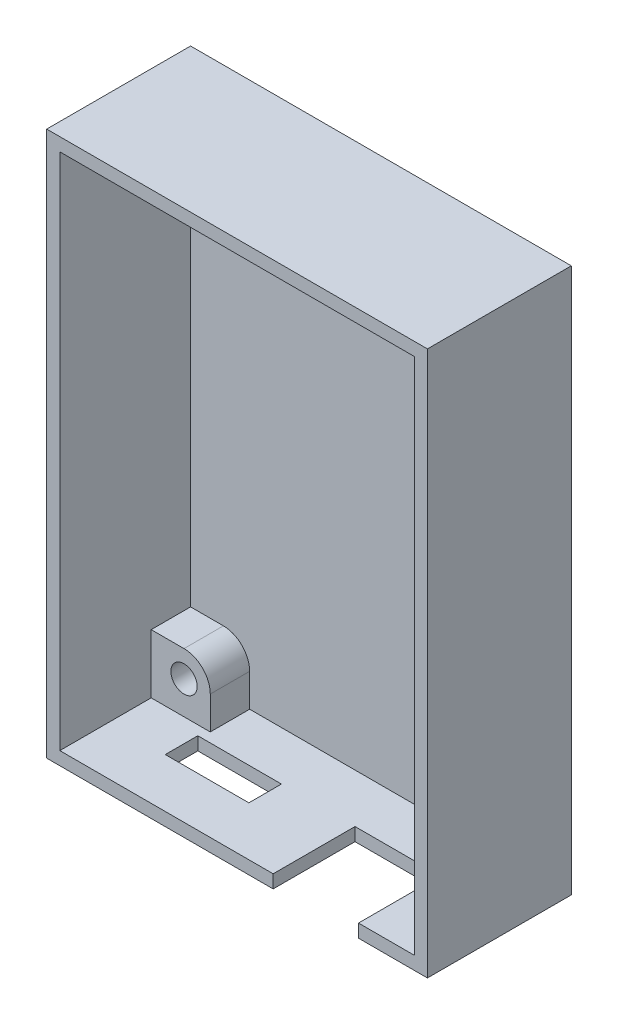
SolidWorks part; units mm, degrees
ref_plane "Front Plane" through (0, 0, 0) normal (1, 0, 0) x (0, 1, 0)
ref_plane "Top Plane" through (0, 0, 0) normal (0, 0, 1) x (0, 1, 0)
ref_plane "Right Plane" through (0, 0, 0) normal (0, 1, 0) x (-1, 0, 0)
sketch "Sketch1" plane through (0, 0, 0) normal (0, 0, 1) x (0, 1, 0)
  line L1 (-41.5, 29) -> (41.5, 29)
  line L2 (-41.5, 29) -> (-41.5, -29)
  line L3 (-41.5, -29) -> (41.5, -29)
  line L4 (41.5, 29) -> (41.5, -29)
  line L5 (-41.5, 29) -> (41.5, -29) construction
  line L6 (-41.5, -29) -> (41.5, 29) construction
  point P0 (0, 0)
  dimension "D1" = 58
  dimension "D2" = 83
extrude "Boss-Extrude1" add sketch "Sketch1" along normal blind 21.92 contours L4 L1 L2 L3
shell "Shell1" thickness 2
sketch "Sketch2" plane through (0, 0, 2) normal (0, 0, 1) x (1, 0, 0)
  line L0 (-27, 39.5) -> (-18, 39.5)
  line L1 (-27, 39.5) -> (27, 39.5) construction
  line L2 (-27, 39.5) -> (-27, 30.5)
  line L3 (-27, 30.5) -> (-22, 30.5)
  line L4 (-18, 39.5) -> (-18, 34.5)
  line L5 (0, 0) -> (50000, 0) construction
  line L6 (0, 0) -> (0, 50000) construction
  line L7 (-20, 34.5) -> (-18, 34.5) construction
  line L9 (24, 34.5) -> (27, 34.5) construction
  line L10 (20, 34.5) -> (18, 34.5) construction
  line L11 (18, 39.5) -> (18, 34.5)
  line L12 (27, 30.5) -> (22, 30.5)
  line L13 (27, 39.5) -> (27, 30.5)
  line L14 (27, 39.5) -> (18, 39.5)
  line L15 (20, -34.5) -> (18, -34.5) construction
  line L16 (24, -34.5) -> (27, -34.5) construction
  line L17 (-24, -34.5) -> (-27, -34.5) construction
  line L18 (-20, -34.5) -> (-18, -34.5) construction
  line L19 (27, -39.5) -> (18, -39.5)
  line L20 (27, -39.5) -> (27, -30.5)
  line L21 (27, -30.5) -> (22, -30.5)
  line L22 (18, -39.5) -> (18, -34.5)
  line L23 (-18, -39.5) -> (-18, -34.5)
  line L24 (-27, -30.5) -> (-22, -30.5)
  line L25 (-27, -39.5) -> (-27, -30.5)
  line L26 (-27, -39.5) -> (-18, -39.5)
  arc A1 (-18, 34.5) -> (-22, 30.5) centre (-22, 34.5) cw
  circle A2 centre (-22, 34.5) radius 2
  circle A3 centre (22, 34.5) radius 2
  arc A4 (18, 34.5) -> (22, 30.5) centre (22, 34.5) ccw
  arc A5 (18, -34.5) -> (22, -30.5) centre (22, -34.5) cw
  circle A6 centre (22, -34.5) radius 2
  circle A7 centre (-22, -34.5) radius 2
  arc A8 (-18, -34.5) -> (-22, -30.5) centre (-22, -34.5) ccw
  dimension "D1" = 2
  dimension "D2" = 4
  dimension "D3" = 22
  dimension "D4" = 34.5
extrude "Boss-Extrude2" add sketch "Sketch2" along normal blind 6 contours L12 A4 L11 L14 L13
sketch "Sketch3" plane through (0, -41.5, 0) normal (0, -1, 0) x (1, 0, 0)
  line L7 (0, 8) -> (0, 0) construction
  line L8 (-18.45, 9.45) -> (-5.71, 9.45)
  line L9 (-18.45, 9.45) -> (-18.45, 14.41)
  line L10 (-18.45, 14.41) -> (-5.71, 14.41)
  line L11 (-5.71, 9.45) -> (-5.71, 14.41)
  line L12 (5.5, 9.45) -> (18.5, 9.45)
  line L13 (5.5, 9.45) -> (5.5, 22.45)
  line L14 (5.5, 22.45) -> (18.5, 22.45)
  line L15 (18.5, 9.45) -> (18.5, 22.45)
  line L16 (-25, 9.45) -> (25, 9.45) construction
  line L17 (-25, 9.45) -> (-25, 8) construction
  line L18 (-25, 8) -> (25, 8) construction
  line L19 (25, 9.45) -> (25, 8) construction
  line L20 (-29, 0) -> (29, 0) construction
  point P8 (-12.08, 14.41)
  point P9 (12, 22.45)
  dimension "D4" = 12.74
  dimension "D5" = 4.96
  dimension "D6" = 13
  dimension "D7" = 13
  dimension "D1" = 8
  dimension "D2" = 1.45
  dimension "D3" = 50
  dimension "D8" = 12.92
  dimension "D9" = 13
extrude "Cut-Extrude1" cut sketch "Sketch3" against normal up to surface (2 mm away) contours L10 L11 L8 L9
equation "\"FPGA_Case_Spacing\"= 2mm"
equation "\"FPGA_Width\"= 50mm"
equation "\"FPGA_Length\"= 75mm"
equation "\"FPGA_Mtn_Hole_Dia\"= 2.7mm"
equation "\"FPGA_Mtn_Hole_Ring_Dia\"= 5mm"
equation "\"D2@Sketch1\"=2*\"FPGA_Case_Spacing\"+\"FPGA_Length\"+\"Case_Thickness\"*2"
equation "\"D1@Sketch1\"=2*\"FPGA_Case_Spacing\"+\"FPGA_Width\"+\"Case_Thickness\"*2"
equation "\"Case_Thickness\"= 2mm"
equation "\"FPGA_Board_Thickness\"= 1.45mm"
equation "\"FPGA_Space_Under\"= 3.27mm"
equation "\"FPGA_Space_Above\"= 11.2mm"
equation "\"Total_Case_Height\"= 2 * \"FPGA_Case_Spacing\" + \"FPGA_Space_Above\" + \"FPGA_Space_Under\" + \"FPGA_Board_Thickness\" + \"Insert_Depth_Space\""
equation "\"D1@Boss-Extrude1\"=\"Total_Case_Height\""
equation "\"D1@Shell1\"=\"Case_Thickness\""
equation "\"Insert_Dia\"= 4mm"
equation "\"Insert_Depth_Min\"= 4mm"
equation "\"Insert_Depth_Space\"= 2mm"
equation "\"D2@Sketch2\"=\"Insert_Dia\""
equation "\"FPGA_Mtn_Hole_Spacing_W\"= 44mm"
equation "\"FPGA_Mtn_Hole_Spacing_L\"= 69mm"
equation "\"D3@Sketch2\"=\"FPGA_Mtn_Hole_Spacing_W\"/2"
equation "\"D4@Sketch2\"=\"FPGA_Mtn_Hole_Spacing_L\"/2"
equation "\"D1@Boss-Extrude2\"=\"Insert_Depth_Space\"+\"Insert_Depth_Min\""
equation "\"D1@Sketch3\"=\"Insert_Depth_Space\"+\"Insert_Depth_Min\"+\"Case_Thickness\""
equation "\"D2@Sketch3\"=\"FPGA_Board_Thickness\""
equation "\"D3@Sketch3\"=\"FPGA_Width\""
